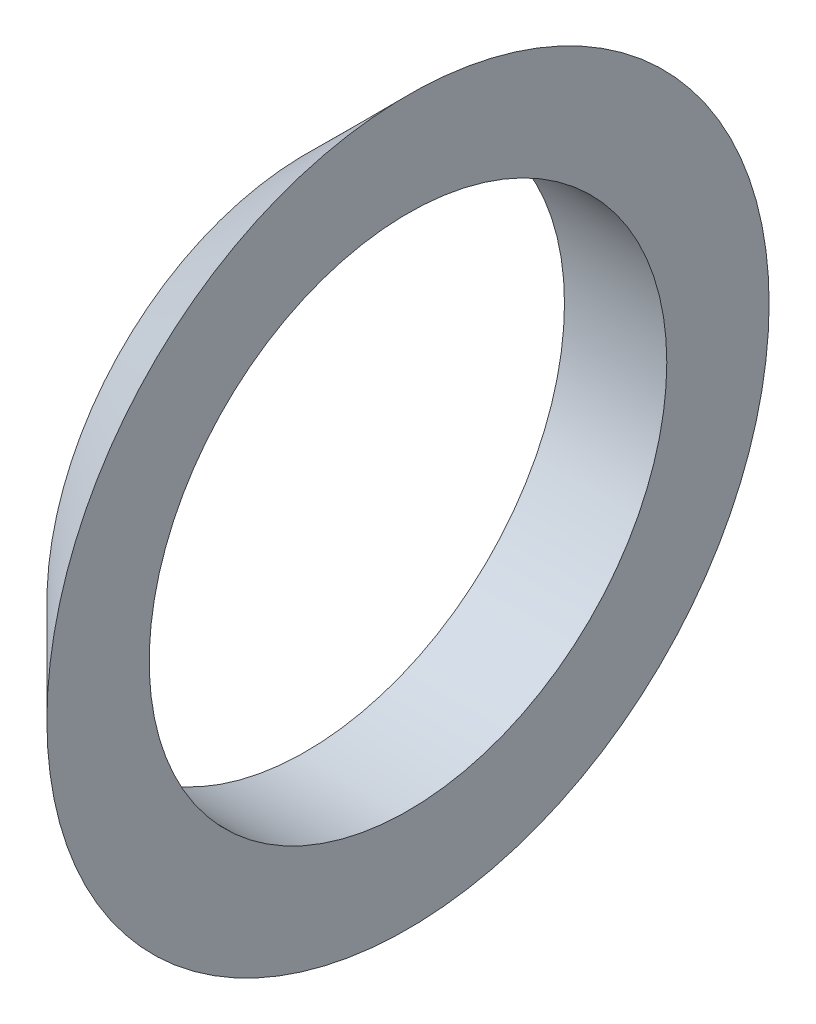
SolidWorks part; units mm, degrees
ref_plane "Front Plane" through (0, 0, 0) normal (1, 0, 0) x (0, 1, 0)
ref_plane "Top Plane" through (0, 0, 0) normal (0, 0, 1) x (0, 1, 0)
ref_plane "Right Plane" through (0, 0, 0) normal (0, 1, 0) x (-1, 0, 0)
sketch "Sketch2" plane through (0, 0, 0) normal (0, 0, 1) x (0, 1, 0)
  line L0 (-76.2, 0) -> (-54.61, 0)
  line L1 (-54.61, 0) -> (-54.61, 21.59)
  line L2 (-54.61, 21.59) -> (-76.2, 0)
  line L4 (0, 0) -> (0, 80.6421) construction
  point P2 (-76.2, 9.1564)
  point P8 (-76.8827, -0.8589)
  dimension "D1" = 54.61
  dimension "D2" = 76.2
  dimension "D3" = 21.59
revolve "Revolve2" add sketch "Sketch2" angle 360 about L4
